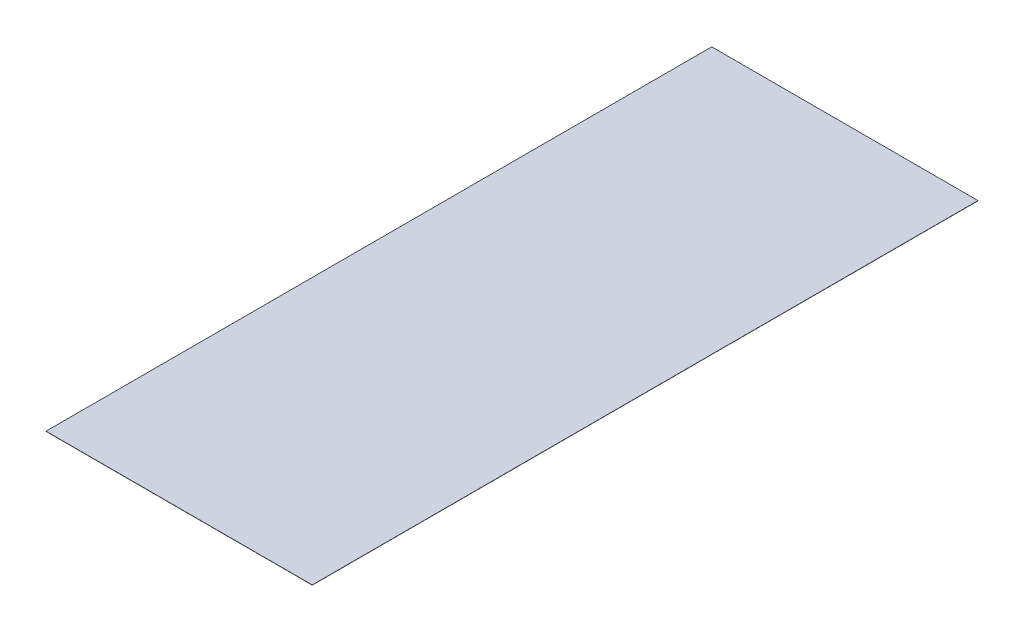
SolidWorks part; units mm, degrees
ref_plane "Front Plane" through (0, 0, 0) normal (0, 0, 1) x (1, 0, 0)
ref_plane "Top Plane" through (0, 0, 0) normal (0, 1, 0) x (1, 0, 0)
ref_plane "Right Plane" through (0, 0, 0) normal (1, 0, 0) x (0, 0, -1)
sketch "Sketch1" plane through (0, 0, 0) normal (0, 1, 0) x (1, 0, 0)
  line L1 (-609.6, 1524) -> (609.6, 1524)
  line L2 (-609.6, 1524) -> (-609.6, -1524)
  line L3 (-609.6, -1524) -> (609.6, -1524)
  line L4 (609.6, 1524) -> (609.6, -1524)
  line L5 (-609.6, 1524) -> (609.6, -1524) construction
  line L6 (-609.6, -1524) -> (609.6, 1524) construction
  point P0 (0, 0)
  dimension "D1" = 3048
  dimension "D2" = 1219.2
extrude "Boss-Extrude1" add sketch "Sketch1" along normal blind 0.912
